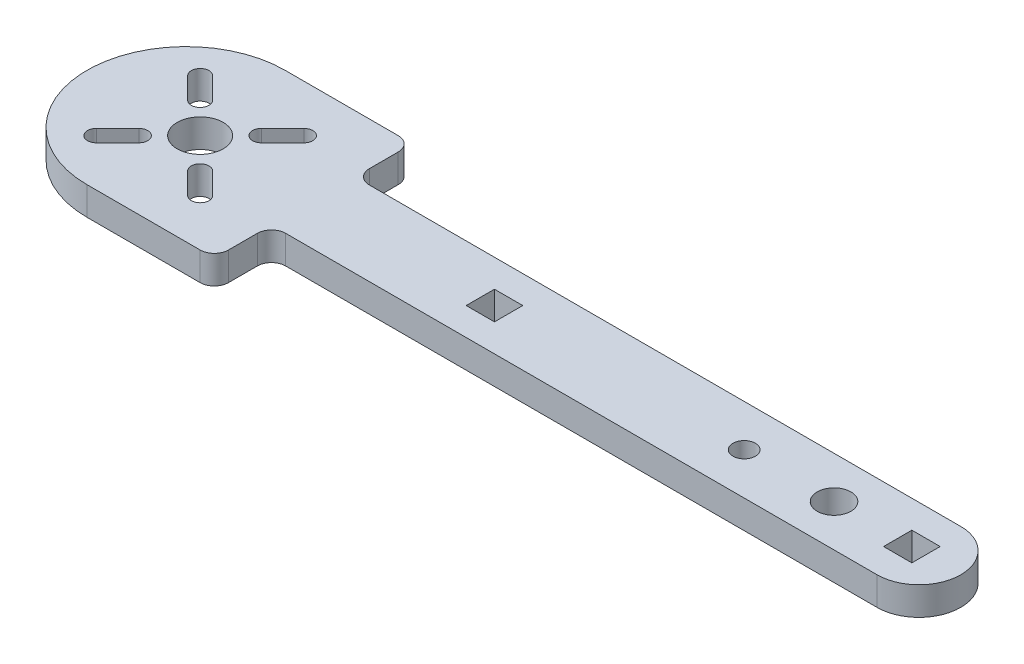
SolidWorks part; units mm, degrees
material "Thornel VCB-20 Carbon Cloth"
ref_plane "Front Plane" through (0, 0, 0) normal (0, 0, 1) x (1, 0, 0)
ref_plane "Top Plane" through (0, 0, 0) normal (0, 1, 0) x (1, 0, 0)
ref_plane "Right Plane" through (0, 0, 0) normal (1, 0, 0) x (0, 0, -1)
sketch "Sketch1" plane through (0, 0, 0) normal (0, 1, 0) x (1, 0, 0)
  line L0 (-58.0134, 7.2134) -> (-43.5866, -7.2134) construction
  line L1 (-50.8, 14) -> (-36.8, 14)
  line L2 (-50.8, 14) -> (-50.8, -14) construction
  line L3 (-50.8, -14) -> (-36.8, -14)
  line L7 (-58.4887, -7.6887) -> (-43.1113, 7.6887) construction
  line L8 (-58.1362, 7.3362) -> (-55.131, 4.331) construction
  line L9 (-57.2523, 8.2201) -> (-54.2471, 5.2149)
  line L10 (-59.0201, 6.4523) -> (-56.0149, 3.4471)
  line L11 (-43.4638, 7.3362) -> (-46.469, 4.331) construction
  line L12 (-42.5799, 6.4523) -> (-45.5851, 3.4471)
  line L13 (-44.3477, 8.2201) -> (-47.3529, 5.2149)
  line L14 (-43.4638, -7.3362) -> (-46.469, -4.331) construction
  line L15 (-44.3477, -8.2201) -> (-47.3529, -5.2149)
  line L16 (-42.5799, -6.4523) -> (-45.5851, -3.4471)
  line L17 (-58.1362, -7.3362) -> (-55.131, -4.331) construction
  line L18 (-59.0201, -6.4523) -> (-56.0149, -3.4471)
  line L19 (-57.2523, -8.2201) -> (-54.2471, -5.2149)
  line L21 (-34.8, 7.9146) -> (-34.8, 12)
  line L24 (-34.8, -12) -> (-34.8, -7.9146)
  line L32 (-32.8, 5.9146) -> (50.8, 5.9146)
  line L33 (-32.8, -5.9146) -> (50.8, -5.9146)
  line L34 (-50.8, 0) -> (50.8, 0) construction
  line L35 (-50.8, 14) -> (-52.8, 14)
  line L36 (-50.8, -14) -> (-52.8, -14)
  line L38 (47.8, -2) -> (51.8, -2)
  line L39 (47.8, -2) -> (47.8, 2)
  line L40 (47.8, 2) -> (51.8, 2)
  line L41 (51.8, -2) -> (51.8, 2)
  line L42 (47.8, -2) -> (51.8, 2) construction
  line L43 (47.8, 2) -> (51.8, -2) construction
  line L44 (-11.2, -2) -> (-7.2, -2)
  line L45 (-11.2, -2) -> (-11.2, 2)
  line L46 (-11.2, 2) -> (-7.2, 2)
  line L47 (-7.2, -2) -> (-7.2, 2)
  line L48 (-11.2, -2) -> (-7.2, 2) construction
  line L49 (-11.2, 2) -> (-7.2, -2) construction
  circle A2 centre (-50.8, 0) radius 3.25
  arc A3 (-57.2523, 8.2201) -> (-59.0201, 6.4523) centre (-58.1362, 7.3362) ccw
  arc A4 (-56.0149, 3.4471) -> (-54.2471, 5.2149) centre (-55.131, 4.331) ccw
  arc A5 (-42.5799, 6.4523) -> (-44.3477, 8.2201) centre (-43.4638, 7.3362) ccw
  arc A6 (-47.3529, 5.2149) -> (-45.5851, 3.4471) centre (-46.469, 4.331) ccw
  arc A7 (-44.3477, -8.2201) -> (-42.5799, -6.4523) centre (-43.4638, -7.3362) ccw
  arc A8 (-45.5851, -3.4471) -> (-47.3529, -5.2149) centre (-46.469, -4.331) ccw
  arc A9 (-59.0201, -6.4523) -> (-57.2523, -8.2201) centre (-58.1362, -7.3362) ccw
  arc A10 (-54.2471, -5.2149) -> (-56.0149, -3.4471) centre (-55.131, -4.331) ccw
  arc A12 (-34.8, -7.9146) -> (-32.8, -5.9146) centre (-32.8, -7.9146) cw
  arc A13 (-32.8, 5.9146) -> (-34.8, 7.9146) centre (-32.8, 7.9146) cw
  arc A14 (-36.8, -14) -> (-34.8, -12) centre (-36.8, -12) ccw
  arc A15 (-34.8, 12) -> (-36.8, 14) centre (-36.8, 12) ccw
  arc A16 (50.8, 5.9146) -> (50.8, -5.9146) centre (50.8, 0) cw
  arc A17 (-52.8, -14) -> (-52.8, 14) centre (-52.8, 0) cw
  circle A18 centre (38.8, 0) radius 2.3812
  circle A19 centre (26.1, 0) radius 1.5875
  point P0 (0, 0)
  point P12 (-50.8, 0)
  point P14 (-50.8, 0)
  point P17 (-56.6336, 5.8336)
  point P27 (-44.9664, 5.8336)
  point P34 (-44.9664, -5.8336)
  point P41 (-56.6336, -5.8336)
  point P46 (-50.8, 0)
  point P53 (-34.8, -7)
  point P56 (-34.8, 7)
  point P59 (-34.8, -14)
  point P62 (-34.8, 14)
  point P64 (49.8, 0)
  point P70 (-9.2, 0)
  dimension "D3" = 6.5
  dimension "D6" = 8.25
  dimension "D10" = 4.7625
  dimension "D17" = 2
  dimension "D18" = 2
  dimension "D16" = 5.9146
  dimension "D2" = 14
  dimension "D21" = 4
  dimension "D22" = 4
  dimension "D27" = 3.175
  dimension "D4" = 45
  dimension "D5" = 45
  dimension "D7" = 4.25
  dimension "D8" = 2.5
  dimension "D11" = 16
  dimension "D12" = 16
  dimension "D13" = 7
  dimension "D14" = 7
  dimension "D15" = 101.6
  dimension "D19" = 50.8
  dimension "D20" = 2
  dimension "D23" = 1
  dimension "D24" = 12
  dimension "D25" = 4
  dimension "D26" = 60
  dimension "D28" = 12.7
  dimension "D9" = 4
extrude "Boss-Extrude1" add sketch "Sketch1" along normal blind 4
